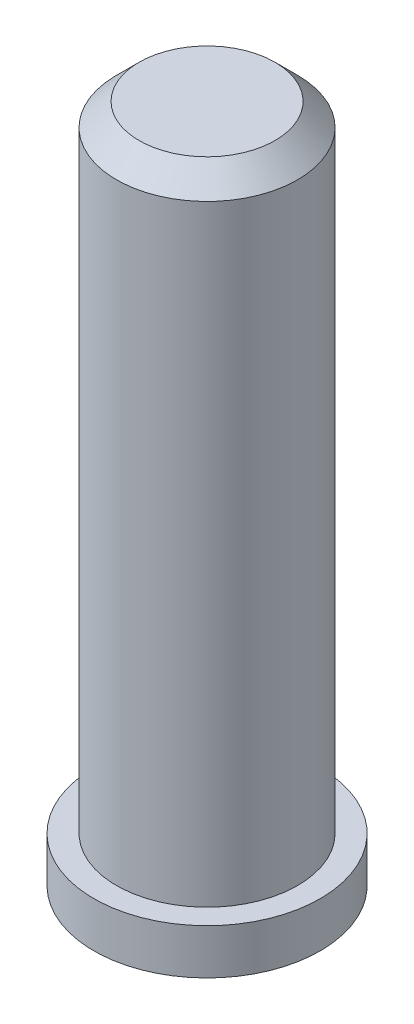
SolidWorks part; units mm, degrees
ref_plane "Front Plane" through (0, 0, 0) normal (0, 0, 1) x (1, 0, 0)
ref_plane "Top Plane" through (0, 0, 0) normal (0, 1, 0) x (1, 0, 0)
ref_plane "Right Plane" through (0, 0, 0) normal (1, 0, 0) x (0, 0, -1)
sketch "Sketch1" plane through (0, 0, 0) normal (1, 0, 0) x (0, 0, -1)
  line L0 (0, -1) -> (0, 29)
  line L1 (-5, -1) -> (5, -1)
  line L2 (-5, -1) -> (-5, 1)
  line L3 (-5, 1) -> (5, 1)
  line L4 (5, -1) -> (5, 1)
  line L5 (-5, -1) -> (5, 1) construction
  line L6 (-5, 1) -> (5, -1) construction
  line L8 (-4, 29) -> (4, 29)
  line L9 (-4, 29) -> (-4, 1)
  line L10 (-4, 1) -> (4, 1)
  line L11 (4, 29) -> (4, 1)
  line L12 (-4, 29) -> (4, 1) construction
  line L13 (-4, 1) -> (4, 29) construction
  point P0 (0, 0)
  point P8 (0, 15)
  point P13 (0, 11.5673)
  dimension "D1" = 2
  dimension "D2" = 10
  dimension "D3" = 8
  dimension "D4" = 30
revolve "Revolve1" add sketch "Sketch1" angle 360 about L0
chamfer "Chamfer1" distance 1 angle 45 1 edges at (0, 29, -4)
